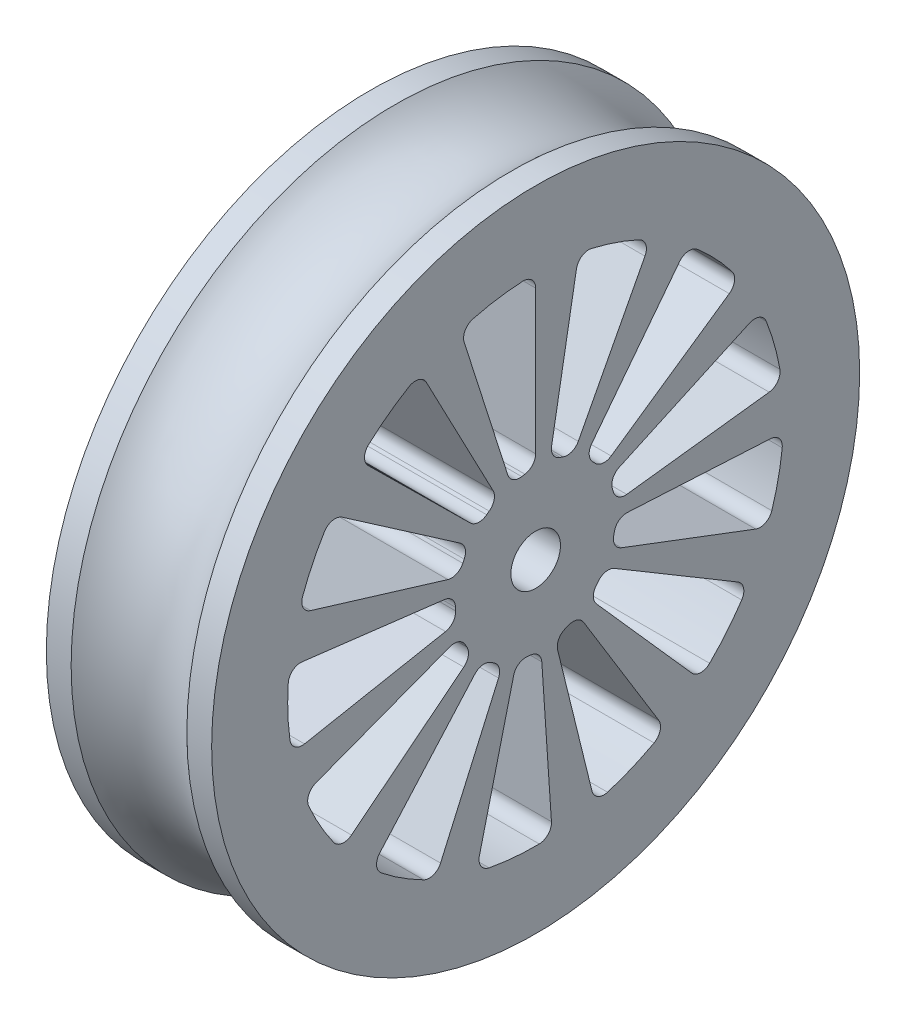
SolidWorks part; units mm, degrees
ref_plane "Front Plane" through (0, 0, 0) normal (0, 0, 1) x (1, 0, 0)
ref_plane "Top Plane" through (0, 0, 0) normal (0, 1, 0) x (1, 0, 0)
ref_plane "Right Plane" through (0, 0, 0) normal (1, 0, 0) x (0, 0, -1)
sketch "Sketch1" plane through (0, 0, 0) normal (0, 0, 1) x (1, 0, 0)
  line L0 (0, 0) -> (10, 0)
  line L1 (0, 0) -> (0, 19.6)
  line L2 (10, 19.6) -> (10, 0)
  line L3 (0, 0) -> (34.8651, 0) construction
  line L4 (0, 19.6) -> (1.5, 19.6)
  line L5 (10, 19.6) -> (8.5, 19.6)
  arc A1 (1.5, 19.6) -> (8.5, 19.6) centre (5, 23.1707) ccw
  dimension "D3" = 1.5
  dimension "D4" = 1.5
  dimension "D5" = 5
  dimension "D1" = 10
  dimension "D2" = 19.6
revolve "Revolve2" add sketch "Sketch1" angle 360 about L3
sketch "Sketch2" plane through (10, 0, 0) normal (1, 0, 0) x (0, 0, -1)
  circle A0 centre (0, 0) radius 1.5
  dimension "D1" = 3
sketch "Sketch3" plane through (10, 0, 0) normal (1, 0, 0) x (0, 0, -1)
  line L0 (0, 0) -> (0, 23.0393) construction
  line L1 (0, 4.8503) -> (0, 15)
  line L2 (0.8423, 4.7766) -> (2.6047, 14.7721)
  line L3 (2.9656, 3.8381) -> (9.1713, 11.8696)
  line L4 (2.2541, 4.2948) -> (6.9708, 13.2818)
  line L5 (4.4096, 2.0203) -> (13.6369, 6.2479)
  line L6 (3.9917, 2.7553) -> (12.3448, 8.521)
  line L7 (4.8433, -0.2603) -> (14.9784, -0.8051)
  line L8 (4.815, 0.5846) -> (14.8906, 1.8081)
  line L9 (4.1676, -2.4813) -> (12.8885, -7.6737)
  line L10 (4.5351, -1.7199) -> (14.0252, -5.3191)
  line L11 (2.5371, -4.1339) -> (7.8461, -12.7843)
  line L12 (3.2164, -3.6305) -> (9.9468, -11.2277)
  line L13 (0.3253, -4.8394) -> (1.0062, -14.9662)
  line L14 (1.1608, -4.7094) -> (3.5897, -14.5641)
  line L15 (-1.9609, -4.4363) -> (-6.0642, -13.7195)
  line L16 (-1.1608, -4.7094) -> (-3.5897, -14.5641)
  line L17 (-3.7979, -3.0169) -> (-11.7454, -9.3298)
  line L18 (-3.2164, -3.6305) -> (-9.9468, -11.2277)
  line L19 (-4.7649, -0.9063) -> (-14.7358, -2.8028)
  line L20 (-4.5351, -1.7199) -> (-14.0252, -5.3191)
  line L21 (-4.6403, 1.4119) -> (-14.3504, 4.3663)
  line L22 (-4.815, 0.5846) -> (-14.8906, 1.8081)
  line L23 (-3.4526, 3.4066) -> (-10.6776, 10.5352)
  line L24 (-3.9917, 2.7553) -> (-12.3448, 8.521)
  line L25 (-1.474, 4.6209) -> (-4.5586, 14.2905)
  line L26 (-2.2541, 4.2948) -> (-6.9708, 13.2818)
  circle A0 centre (0, 0) radius 15
  circle A1 centre (0, 0) radius 4.8503
  point P59 (0, 0)
  dimension "D1" = 15
  dimension "D2" = 10
  dimension "D3" = 13
extrude "Cut-Extrude2" cut sketch "Sketch3" against normal through all contours A1 L4 A0 L2 | A1 L6 A0 L3 | A1 L8 A0 L5 | A1 L10 A0 L7 | A1 L12 A0 L9 | A1 L14 A0 L11 | A1 L16 A0 L13 | A1 L18 A0 L15 | A1 L20 A0 L17 | A1 L22 A0 L19 | A1 L24 A0 L21 | A1 L26 A0 L23 | A1 L1 A0 L25
fillet "Fillet1" radius 0.75 52 edges at (5, 14.2905, 4.5586) (5, 14.7721, -2.6047) (5, 10.5352, 10.6776) (5, 4.3663, 14.3504) (5, 1.8081, 14.8906) (5, -5.3191, 14.0252) (5, -11.2277, 9.9468) (5, -14.5641, 3.5897) (5, -14.5641, -3.5897) (5, 11.8696, -9.1713) (5, -5.3191, -14.0252) (5, -0.8051, -14.9784) (5, 1.8081, -14.8906) (5, 6.2479, -13.6369) (5, 8.521, -12.3448) (5, 13.2818, -6.9708) (5, 15, 0) (5, 13.2818, 6.9708) (5, 8.521, 12.3448) (5, -2.8028, 14.7358) (5, -9.3298, 11.7454) (5, -13.7195, 6.0642) (5, -14.9662, -1.0062) (5, -12.7843, -7.8461) (5, -11.2277, -9.9468) (5, -7.6737, -12.8885) (5, 4.6209, 1.474) (5, 4.8503, 0) (5, 3.4066, 3.4526) (5, 4.2948, 2.2541) (5, 1.4119, 4.6403) (5, 2.7553, 3.9917) (5, -0.9063, 4.7649) (5, 0.5846, 4.815) (5, -3.0169, 3.7979) (5, -1.7199, 4.5351) (5, -3.6305, 3.2164) (5, -4.4363, 1.9609) (5, -4.7094, 1.1608) (5, -4.8394, -0.3253) (5, -4.7094, -1.1608) (5, -4.1339, -2.5371) (5, -3.6305, -3.2164) (5, -2.4813, -4.1676) (5, -1.7199, -4.5351) (5, -0.2603, -4.8433) (5, 0.5846, -4.815) (5, 2.0203, -4.4096) (5, 2.7553, -3.9917) (5, 4.7766, -0.8423) (5, 4.2948, -2.2541) (5, 3.8381, -2.9656)
sketch "Sketch4" plane through (10, 0, 0) normal (1, 0, 0) x (0, 0, -1)
extrude "Cut-Extrude3" cut sketch "Sketch2" against normal through all and the other way through all
